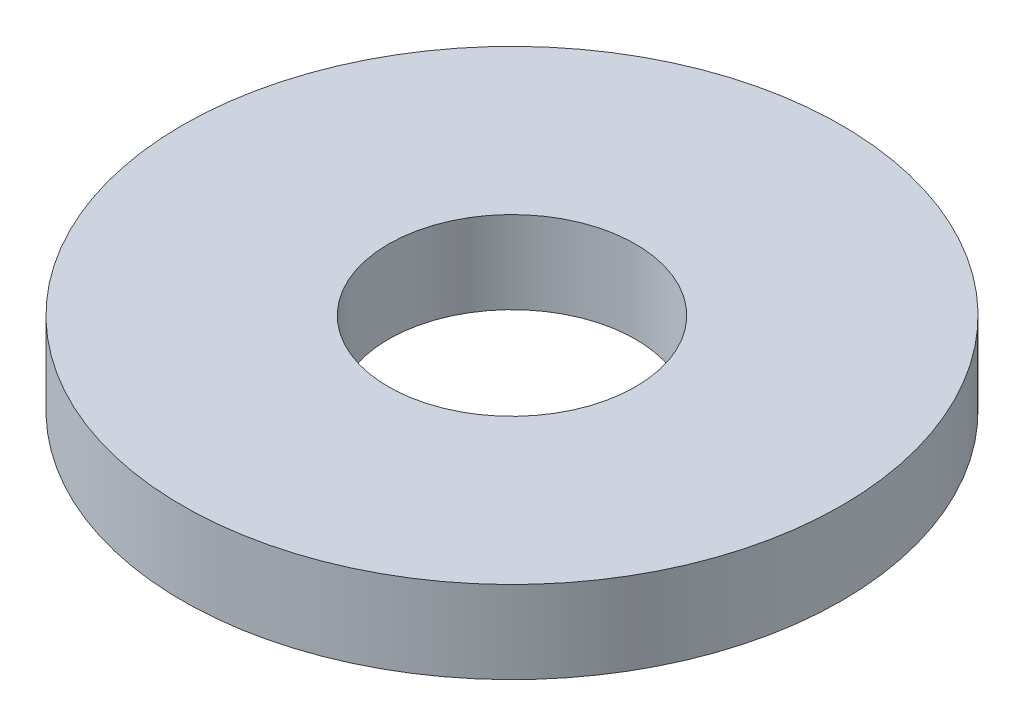
SolidWorks part; units mm, degrees
material "2.0371 (CuZn38Pb2)"
ref_plane "Plan de face" through (0, 0, 0) normal (0, 0, 1) x (1, 0, 0)
ref_plane "Plan de dessus" through (0, 0, 0) normal (0, 1, 0) x (1, 0, 0)
ref_plane "Plan de droite" through (0, 0, 0) normal (1, 0, 0) x (0, 0, -1)
sketch "base" plane through (0, 0, 0) normal (0, 0, 1) x (1, 0, 0)
  line L0 (0, -0.5) -> (0, 0.5) construction
  line L1 (1.5, 0.5) -> (4, 0.5)
  line L2 (1.5, 0.5) -> (1.5, -0.5)
  line L3 (1.5, -0.5) -> (4, -0.5)
  line L4 (4, 0.5) -> (4, -0.5)
  line L5 (0, 0) -> (1.5, 0) construction
  line L6 (1.5, 0) -> (4, 0) construction
  point P8 (0, 0)
  dimension "W" = 2.5
  dimension "H" = 1
  dimension "R" = 1.5
revolve "Revolution" add sketch "base" angle 360 about L0
equation "\"R@base\"= \"magnet_H\" / 2"
equation "\"W@base\" =  ( \"magnet_DE\" - \"magnet_DI\" )  / 2"
equation "\"H@base\" = \"gap_magnet_H\""
equation "\"magnet_DI\"= 3mm'inner diameter of the o-ring magnet"
equation "\"magnet_DE\"= 8mm'external diameter of the o-ring magnet"
equation "\"magnet_H\"= 3mm'tall of the magnet"
equation "\"gap_magnet_H\"= 1mm'gap between the 2 magnets"
equation "\"plug_DI\"= 1.5mm'size of the inner extrude of the plug (finger contact)"
